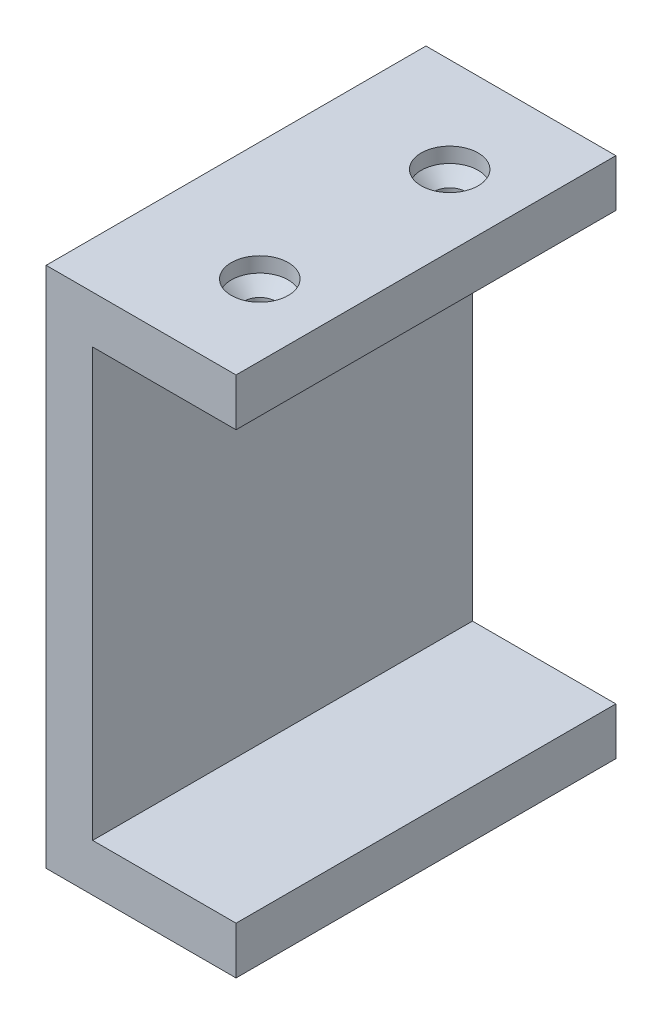
SolidWorks part; units mm, degrees
ref_plane "Front Plane" through (0, 0, 0) normal (0, 0, 1) x (1, 0, 0)
ref_plane "Top Plane" through (0, 0, 0) normal (0, 1, 0) x (1, 0, 0)
ref_plane "Right Plane" through (0, 0, 0) normal (1, 0, 0) x (0, 0, -1)
sketch "Sketch1" plane through (0, 0, 0) normal (0, 1, 0) x (1, 0, 0)
  line L0 (-7.5, -20) -> (7.5, -20)
  line L2 (7.5, -20) -> (7.5, 20)
  line L3 (-7.5, 20) -> (7.5, 20)
  line L4 (-7.5, -20) -> (7.5, 20) construction
  line L5 (7.5, -20) -> (-7.5, 20) construction
  line L6 (-12.5, 20) -> (-7.5, 20)
  line L10 (-12.5, 20) -> (-12.5, -20)
  line L11 (-7.5, -20) -> (-12.5, -20)
  point P1 (0, 0)
extrude "Boss-Extrude1" add sketch "Sketch1" along normal blind 5
sketch "Sketch2" plane through (0, 0, 0) normal (0, 1, 0) x (1, 0, 0)
  line L1 (-7.6, 20) -> (-12.5, 20)
  line L2 (-7.6, 20) -> (-7.6, -20)
  line L3 (-7.6, -20) -> (-12.5, -20)
  line L4 (-12.5, 20) -> (-12.5, -20)
extrude "Boss-Extrude2" add sketch "Sketch2" against normal blind 45
sketch "Sketch3" plane through (0, -45, 0) normal (0, -1, 0) x (1, 0, 0)
  line L1 (-12.5, -20) -> (7.5, -20)
  line L2 (-12.5, -20) -> (-12.5, 20)
  line L3 (-12.5, 20) -> (7.5, 20)
  line L4 (7.5, -20) -> (7.5, 20)
extrude "Boss-Extrude3" add sketch "Sketch3" along normal blind 5
sketch "Sketch4" plane through (0, 0, 0) normal (0, -1, 0) x (1, 0, 0)
  line L0 (0, 0) -> (0, -20) construction
  line L1 (2.75, 0) -> (-2.75, 0) construction
  circle A2 centre (0, -10) radius 3
  circle A3 centre (0, 10) radius 3
extrude "Cut-Extrude1" cut sketch "Sketch4" against normal blind 5
ref_axis "Axis2" through (0, 5, 10) along (0, -1, 0)
ref_plane "Plane1" through (0, 0, 0) normal (-1, 0, 0) x (0, -1, 0)
sketch "Sketch5" plane through (0, 0, 0) normal (-1, 0, 0) x (0, -1, 0)
  line L0 (-3.415, 13) -> (-2.115, 11.7)
  line L2 (0, 11.7) -> (0, 13)
  line L4 (-2.115, 11.7) -> (1, 11.7)
  line L5 (1, 8.3) -> (-2.115, 8.3)
  line L7 (-2.115, 11.7) -> (0, 11.7)
  line L8 (-3.415, 13) -> (0, 13)
revolve "Revolve1" add sketch "Sketch5" angle 360 about axis through (0, 5, 10) along (0, -1, 0)
mirror "Mirror1" about plane through (0, 0, 0) normal (0, 0, 1) of "Revolve1"
